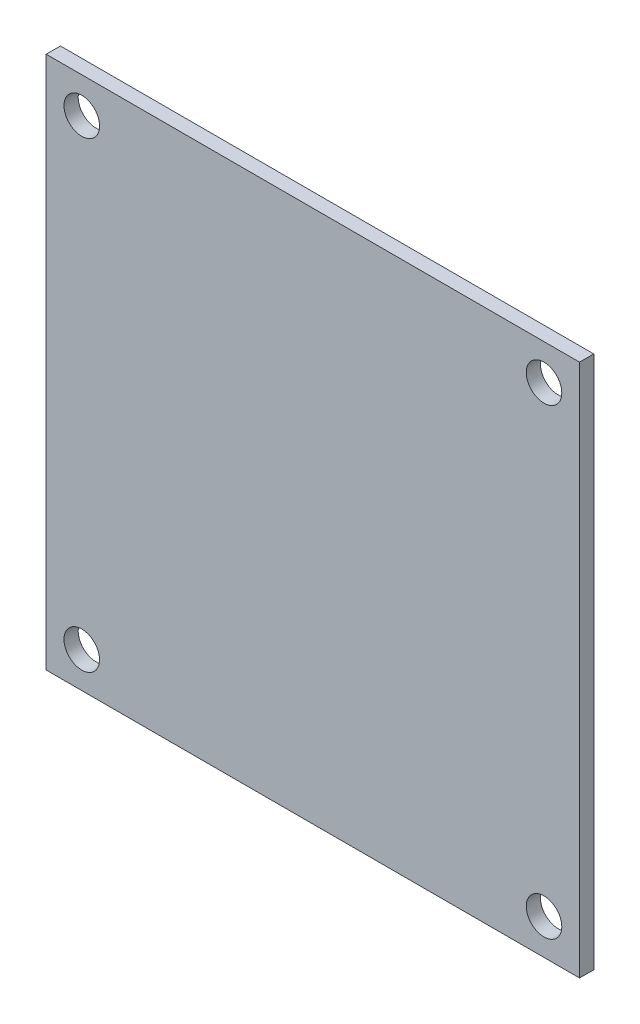
SolidWorks part; units mm, degrees
ref_plane "Plan de face" through (0, 0, 0) normal (0, 0, 1) x (1, 0, 0)
ref_plane "Plan de dessus" through (0, 0, 0) normal (0, 1, 0) x (1, 0, 0)
ref_plane "Plan de droite" through (0, 0, 0) normal (1, 0, 0) x (0, 0, -1)
sketch "Esquisse1" plane through (0, 0, 0) normal (0, 0, 1) x (1, 0, 0)
  line L1 (-35.6564, 38.1752) -> (39.3436, 38.1752)
  line L2 (-35.6564, 38.1752) -> (-35.6564, -36.8248)
  line L3 (-35.6564, -36.8248) -> (39.3436, -36.8248)
  line L4 (39.3436, 38.1752) -> (39.3436, -36.8248)
  dimension "D1" = 75
  dimension "D2" = 75
extrude "Boss.-Extru.1" add sketch "Esquisse1" along normal blind 2
sketch "Esquisse2" plane through (0, 0, 2) normal (0, 0, 1) x (1, 0, 0)
  line L0 (-35.6564, 38.1752) -> (-35.6564, -36.8248) construction
  line L1 (39.3436, 38.1752) -> (-35.6564, 38.1752) construction
  line L2 (-35.6564, -36.8248) -> (39.3436, -36.8248) construction
  line L3 (39.3436, -36.8248) -> (39.3436, 38.1752) construction
  circle A0 centre (-30.6564, 33.1752) radius 2.5
  circle A1 centre (-30.6564, -31.8248) radius 2.5
  circle A2 centre (34.3436, 33.1752) radius 2.5
  circle A3 centre (34.3436, -31.8248) radius 2.5
  dimension "D3" = 5
  dimension "D6" = 5
  dimension "D8" = 5
  dimension "D9" = 5
  dimension "D1" = 5
  dimension "D2" = 5
  dimension "D4" = 5
  dimension "D5" = 5
  dimension "D7" = 5
extrude "Enlèv. mat.-Extru.1" cut sketch "Esquisse2" against normal blind 10
